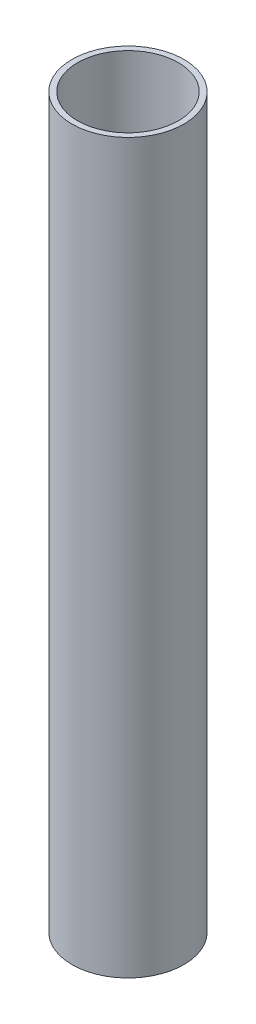
SolidWorks part; units mm, degrees
material "High-Strength Lightweight"
ref_plane "Front Plane" through (0, 0, 0) normal (0, 0, 1) x (1, 0, 0)
ref_plane "Top Plane" through (0, 0, 0) normal (0, 1, 0) x (1, 0, 0)
ref_plane "Right Plane" through (0, 0, 0) normal (1, 0, 0) x (0, 0, -1)
sketch "Sketch1" plane through (0, 0, 0) normal (0, 1, 0) x (1, 0, 0)
  circle A0 centre (0, 0) radius 10
  circle A1 centre (0, 0) radius 9
  dimension "D1" = 20
  dimension "D2" = 18
extrude "Boss-Extrude1" add sketch "Sketch1" along normal blind 130
